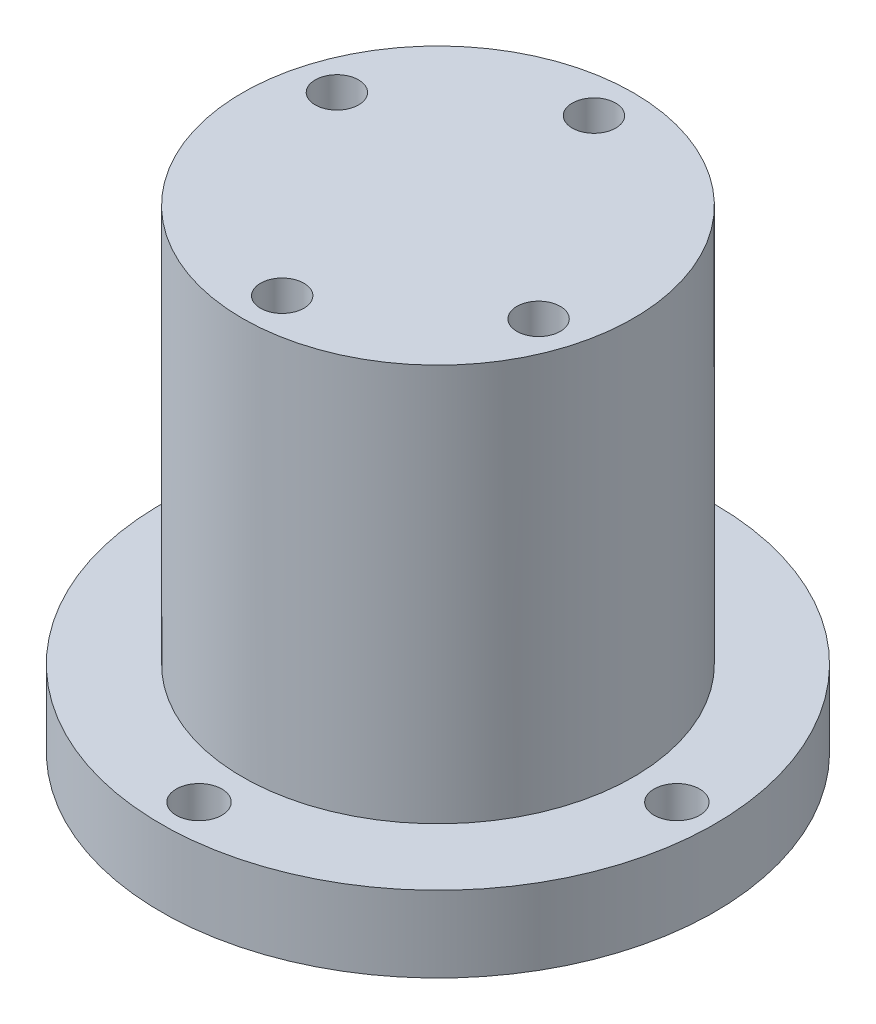
SolidWorks part; units mm, degrees
ref_plane "Спереди" through (0, 0, 0) normal (0, 0, 1) x (1, 0, 0)
ref_plane "Сверху" through (0, 0, 0) normal (0, 1, 0) x (1, 0, 0)
ref_plane "Справа" through (0, 0, 0) normal (1, 0, 0) x (0, 0, -1)
other "Configuration Table"
sketch "Эскиз1" plane through (0, 0, 0) normal (0, 1, 0) x (1, 0, 0)
  circle A0 centre (0, 0) radius 18
extrude "Бобышка-Вытянуть1" add sketch "Эскиз1" along normal blind 43.573
sketch "Эскиз2" plane through (0, 43.573, 0) normal (0, 1, 0) x (1, 0, 0)
  circle A2 centre (0, 0) radius 14.929 construction
  circle A3 centre (0, 0) radius 20.1944 construction
  circle A4 centre (0.0083, 14.3598) radius 2
  circle A5 centre (13.6692, -4.3996) radius 2
  circle A6 centre (0.0189, -14.3598) radius 2
  circle A7 centre (-13.6776, 4.3737) radius 2
sketch "Эскиз3" plane through (0, 0, 0) normal (0, -1, 0) x (1, 0, 0)
  line L0 (0, 0) -> (20, 0) construction
  line L1 (0, 22) -> (0, -22) construction
  circle A0 centre (0, 0) radius 25.5
  circle A1 centre (0, 0) radius 22
  circle A3 centre (0, 22) radius 2.1
  circle A4 centre (-22, 0) radius 2.1
  circle A5 centre (0, -22) radius 2.1
  circle A6 centre (22, 0) radius 2.1
  circle M8 centre (0, 0) radius 18
extrude "Бобышка-Вытянуть2" add sketch "Эскиз3" against normal blind 7 contours A0 A1 A6 A5 A4 A3 | A1 A6 A3 A4 A5 M8
extrude "Вырез-Вытянуть1" cut sketch "Эскиз2" against normal blind 10
